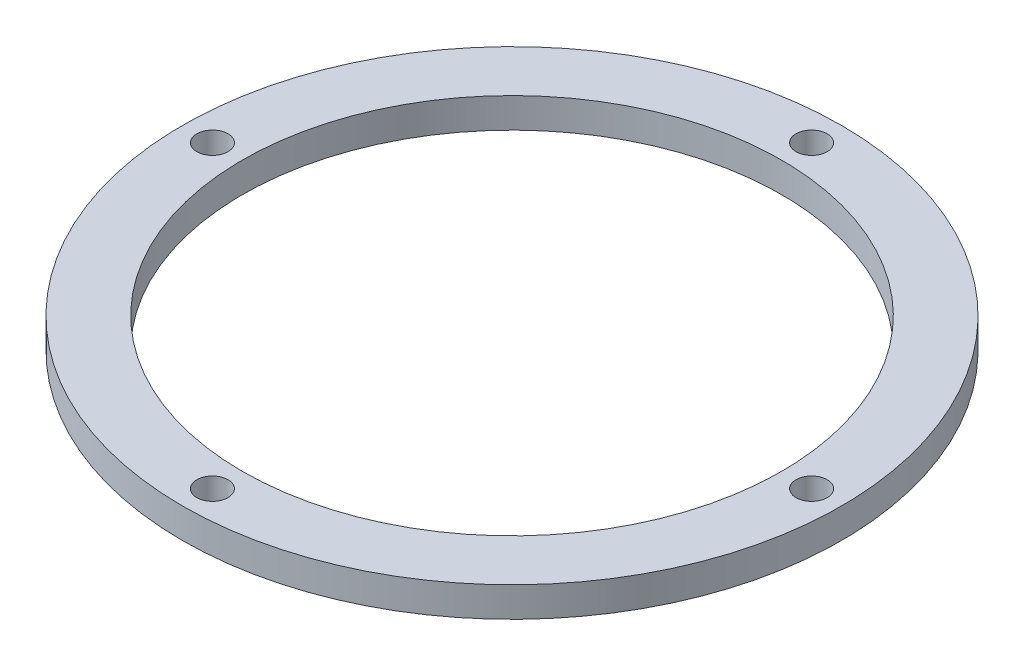
SolidWorks part; units mm, degrees
ref_plane "Front Plane" through (0, 0, 0) normal (0, 0, 1) x (1, 0, 0)
ref_plane "Top Plane" through (0, 0, 0) normal (0, 1, 0) x (1, 0, 0)
ref_plane "Right Plane" through (0, 0, 0) normal (1, 0, 0) x (0, 0, -1)
sketch "Sketch1" plane through (0, 0, 0) normal (0, 1, 0) x (1, 0, 0)
  circle A0 centre (0, 0) radius 45
  circle A1 centre (0, 0) radius 55
  circle A2 centre (0, 50) radius 2.6
  circle A3 centre (50, 0) radius 2.6
  circle A4 centre (0, -50) radius 2.6
  circle A5 centre (-50, 0) radius 2.6
  point P15 (0, 0)
  dimension "D1" = 90
  dimension "D2" = 110
  dimension "D3" = 5.2
  dimension "D4" = 50
  dimension "D5" = 4
extrude "Boss-Extrude1" add sketch "Sketch1" along normal blind 5
